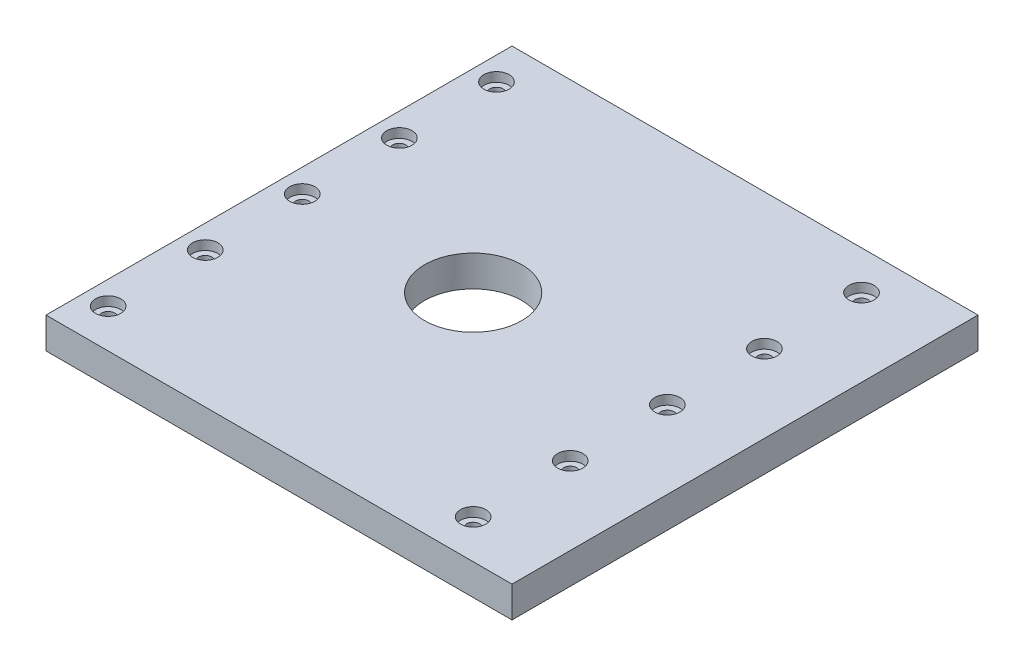
SolidWorks part; units mm, degrees
material "6061-T6 (SS)"
ref_plane "Front Plane" through (0, 0, 0) normal (0, 0, 1) x (1, 0, 0)
ref_plane "Top Plane" through (0, 0, 0) normal (0, 1, 0) x (1, 0, 0)
ref_plane "Right Plane" through (0, 0, 0) normal (1, 0, 0) x (0, 0, -1)
sketch "Sketch1" plane through (0, 0, 0) normal (0, 1, 0) x (1, 0, 0)
  line L1 (0, 0) -> (120, 0)
  line L2 (0, 0) -> (0, 120)
  line L3 (0, 120) -> (120, 120)
  line L4 (120, 0) -> (120, 120)
  dimension "D1" = 120
extrude "Boss-Extrude1" add sketch "Sketch1" along normal blind 8
sketch "Sketch2" plane through (0, 8, 0) normal (0, 1, 0) x (1, 0, 0)
  line L0 (0, 120) -> (6, 120)
  line L1 (120, 120) -> (0, 120) construction
  line L2 (6, 120) -> (6, 0)
  line L3 (0, 0) -> (120, 0) construction
  line L4 (0, 120) -> (0, 0) construction
  line L5 (100, 120) -> (100, 0) construction
  line L7 (120, 0) -> (120, 120) construction
  point P11 (6, 110)
  point P18 (6, 85)
  point P19 (6, 60)
  point P20 (6, 35)
  point P21 (6, 10)
  point P32 (100, 60)
  point P41 (100, 35)
  point P42 (100, 10)
  point P43 (100, 60)
  point P44 (100, 35)
  point P45 (100, 85)
  point P46 (100, 60)
  point P47 (100, 85)
  point P48 (100, 110)
  dimension "D1" = 5
  dimension "D2" = 10
  dimension "D3" = 6
  dimension "D4" = 20
  dimension "D5" = 3
  dimension "D6" = 3
hole_wizard "CBORE for M3 Hex Socket Thin Head Cap Screw1" positions "Sketch2" profile "Sketch3" counterbore size "M3" standard "DIN" end condition through all
sketch "Sketch3" plane through (100, 8, -110) normal (1, 0, 0) x (0, 0, 1)
  line L0 (0, 0) -> (0, 8)
  line L1 (0, 8) -> (1.7, 8)
  line L3 (1.7, 8) -> (1.7, 2.4)
  line L4 (1.7, 2.4) -> (3.25, 2.4)
  line L5 (3.25, 2.4) -> (3.25, 0)
  line L7 (3.25, 0) -> (0, 0)
  line L11 (0, -6.35) -> (0, 107.95) construction
  dimension "Thru Hole Dia." = 3.4
  dimension "Thru Hole Depth" = 8
  dimension "C'Bore Dia." = 6.5
  dimension "C'Bore Depth" = 2.4
sketch "Sketch6" plane through (0, 8, 0) normal (0, 1, 0) x (1, 0, 0)
  line L0 (6, 110) -> (100, 10) construction
  line L1 (100, 10) -> (100, 120)
  line L2 (120, 120) -> (0, 120) construction
  line L3 (100, 120) -> (0, 0)
  line L4 (0, 0) -> (0, 120)
  line L5 (0, 120) -> (96, 0)
  line L6 (0, 0) -> (120, 0) construction
  point P19 (50, 60)
hole_wizard "Ø25.0mm Dowel Hole1" positions "Sketch6" profile "Sketch5" hole size "Ø25.0" standard "DIN"
sketch "Sketch5" plane through (50, 8, -60) normal (1, 0, 0) x (0, 0, 1)
  line L0 (0, 0) -> (0, 17.5108)
  line L1 (0, 17.5108) -> (12.5, 10)
  line L2 (12.5, 10) -> (12.5, 0)
  line L5 (12.5, 0) -> (0, 0)
  line L10 (0, 17.5108) -> (-12.5, 10) construction
  line L11 (0, -6.35) -> (0, 107.95) construction
  dimension "Hole Dia." = 25
  dimension "Hole Depth" = 10
  dimension "Drill Angle" = 118
